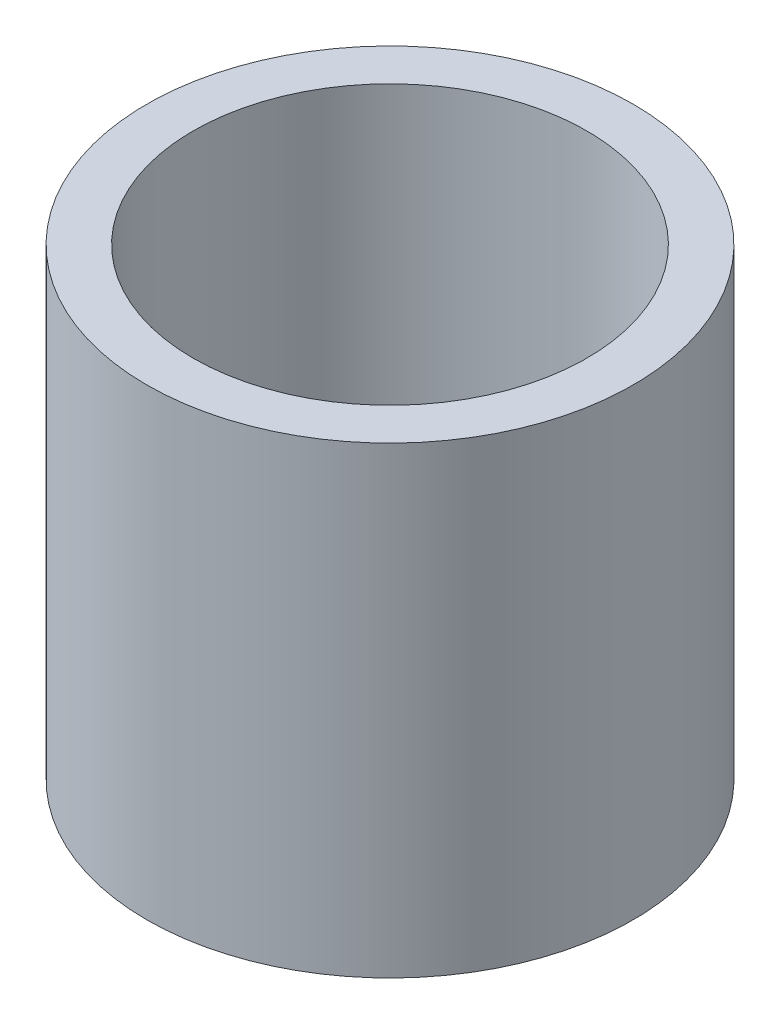
SolidWorks part; units mm, degrees
ref_plane "Front Plane" through (0, 0, 0) normal (0, 0, 1) x (1, 0, 0)
ref_plane "Top Plane" through (0, 0, 0) normal (0, 1, 0) x (1, 0, 0)
ref_plane "Right Plane" through (0, 0, 0) normal (1, 0, 0) x (0, 0, -1)
sketch "Sketch1" plane through (0, 0, 0) normal (0, 1, 0) x (1, 0, 0)
  circle A0 centre (0, 0) radius 2.55
  circle A1 centre (0, 0) radius 3.15
  dimension "D1" = 5.1
  dimension "D2" = 6.3
extrude "Boss-Extrude1" add sketch "Sketch1" along normal blind 6
